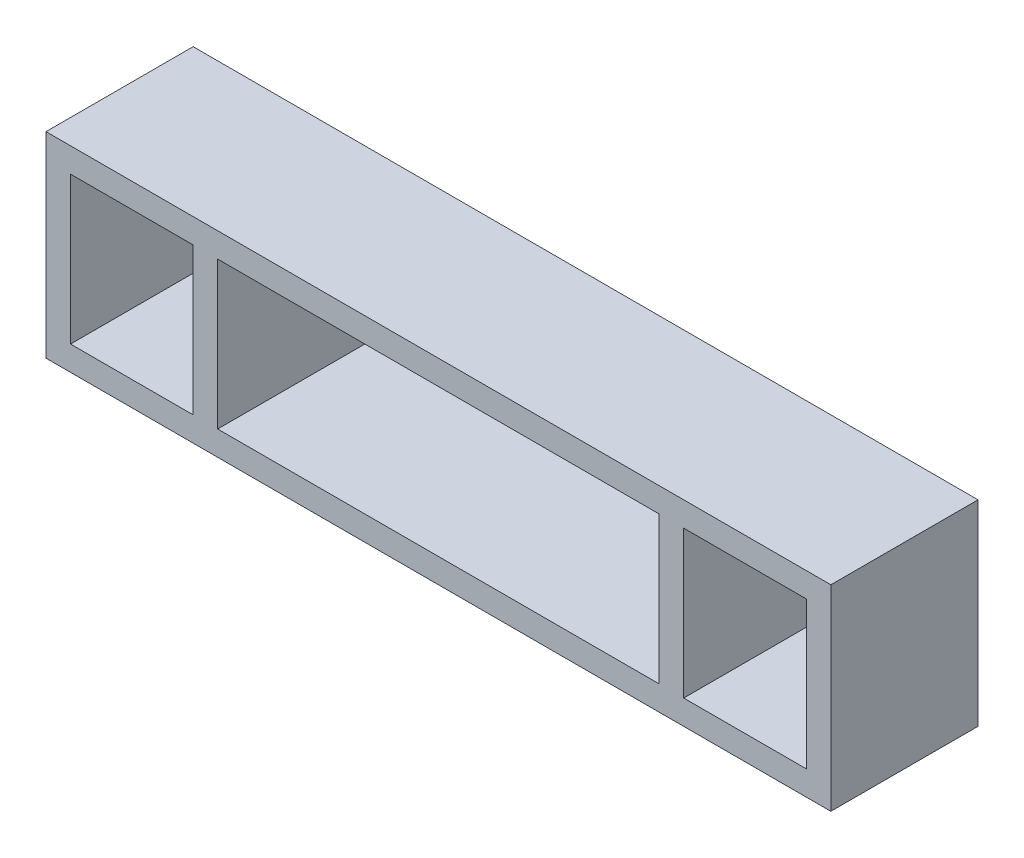
SolidWorks part; units mm, degrees
ref_plane "前视基准面" through (0, 0, 0) normal (0, 0, 1) x (1, 0, 0)
ref_plane "上视基准面" through (0, 0, 0) normal (0, 1, 0) x (1, 0, 0)
ref_plane "右视基准面" through (0, 0, 0) normal (1, 0, 0) x (0, 0, -1)
other "Configuration Table"
sketch "草图8" plane through (0, 0, 0) normal (0, 0, 1) x (1, 0, 0)
  line L0 (0, 0) -> (0, 24.6253) construction
  line L1 (-75, -15) -> (-50, -15)
  line L2 (-75, -15) -> (-75, 15)
  line L3 (-75, 15) -> (-50, 15)
  line L4 (75, -15) -> (75, 15)
  line L5 (-75, -15) -> (75, 15) construction
  line L6 (-75, 15) -> (75, -15) construction
  line L9 (-50, 15) -> (-50, -15)
  line L11 (-45, 15) -> (-45, -15)
  line L12 (45, 15) -> (45, -15)
  line L14 (50, 15) -> (50, -15)
  line L15 (-45, 15) -> (45, 15)
  line L16 (-80, 20) -> (80, 20)
  line L17 (-80, 20) -> (-80, -20)
  line L18 (-80, -20) -> (80, -20)
  line L19 (80, 20) -> (80, -20)
  line L20 (-80, 20) -> (80, -20) construction
  line L21 (-80, -20) -> (80, 20) construction
  line L22 (-45, -15) -> (45, -15)
  line L23 (50, 15) -> (75, 15)
  line L24 (50, -15) -> (75, -15)
  point P0 (0, 0)
  dimension "D1" = 30
  dimension "D2" = 150
  dimension "D3" = 100
  dimension "D4" = 5
  dimension "D5" = 5
  dimension "D6" = 5
extrude "凸台-拉伸5" add sketch "草图8" along normal blind 30
